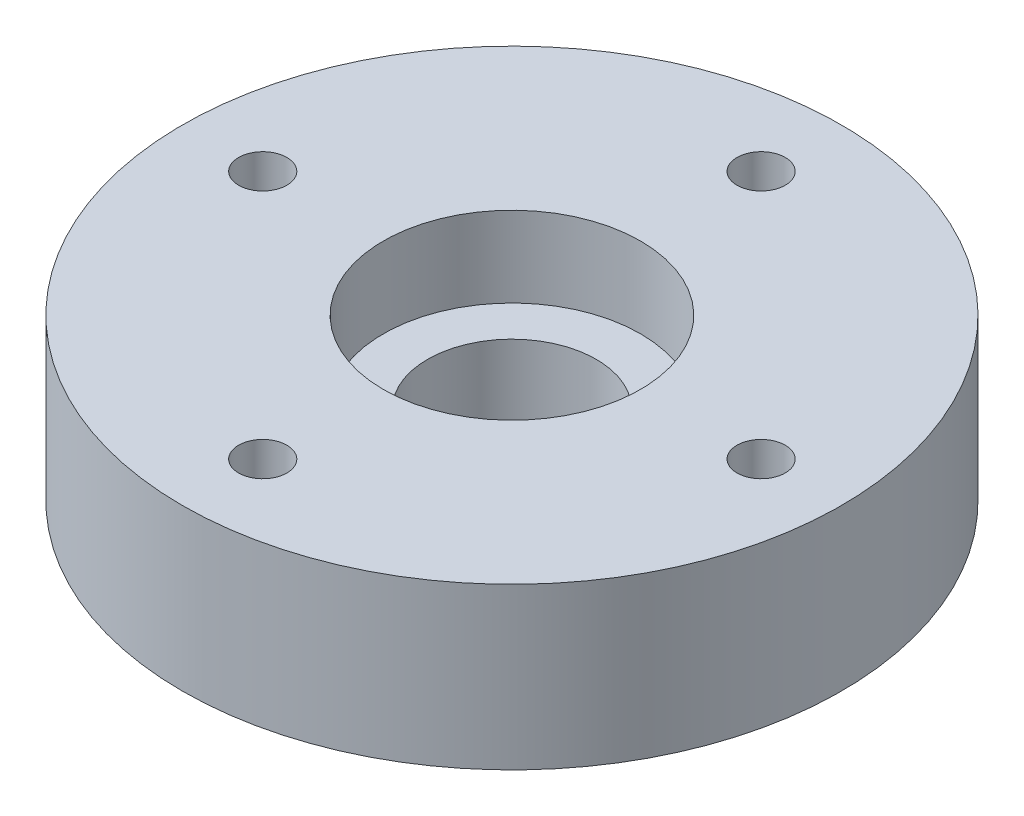
SolidWorks part; units mm, degrees
material "1060 Alloy"
ref_plane "Front Plane" through (0, 0, 0) normal (0, 0, 1) x (1, 0, 0)
ref_plane "Top Plane" through (0, 0, 0) normal (0, 1, 0) x (1, 0, 0)
ref_plane "Right Plane" through (0, 0, 0) normal (1, 0, 0) x (0, 0, -1)
sketch "Sketch1" plane through (0, 0, 0) normal (0, 1, 0) x (1, 0, 0)
  circle A0 centre (0, 0) radius 5.25
  circle A1 centre (0, 0) radius 20.5
  dimension "D1" = 10.5
  dimension "D2" = 41
extrude "Boss-Extrude1" add sketch "Sketch1" along normal blind 10
sketch "Sketch2" plane through (0, 10, 0) normal (0, 1, 0) x (1, 0, 0)
  circle A0 centre (0, 0) radius 8
  dimension "D1" = 16
extrude "Cut-Extrude1" cut sketch "Sketch2" against normal blind 5
sketch "Sketch5" plane through (0, 10, 0) normal (0, 1, 0) x (1, 0, 0)
  circle A0 centre (0, 0) radius 15.5 construction
  circle A1 centre (0, 15.5) radius 1.5
  circle A2 centre (15.5, 0) radius 1.5
  circle A3 centre (0, -15.5) radius 1.5
  circle A4 centre (-15.5, 0) radius 1.5
  point P14 (0, 0)
  dimension "D1" = 31
  dimension "D2" = 3
  dimension "D3" = 4
extrude "Cut-Extrude2" cut sketch "Sketch5" against normal blind 10
